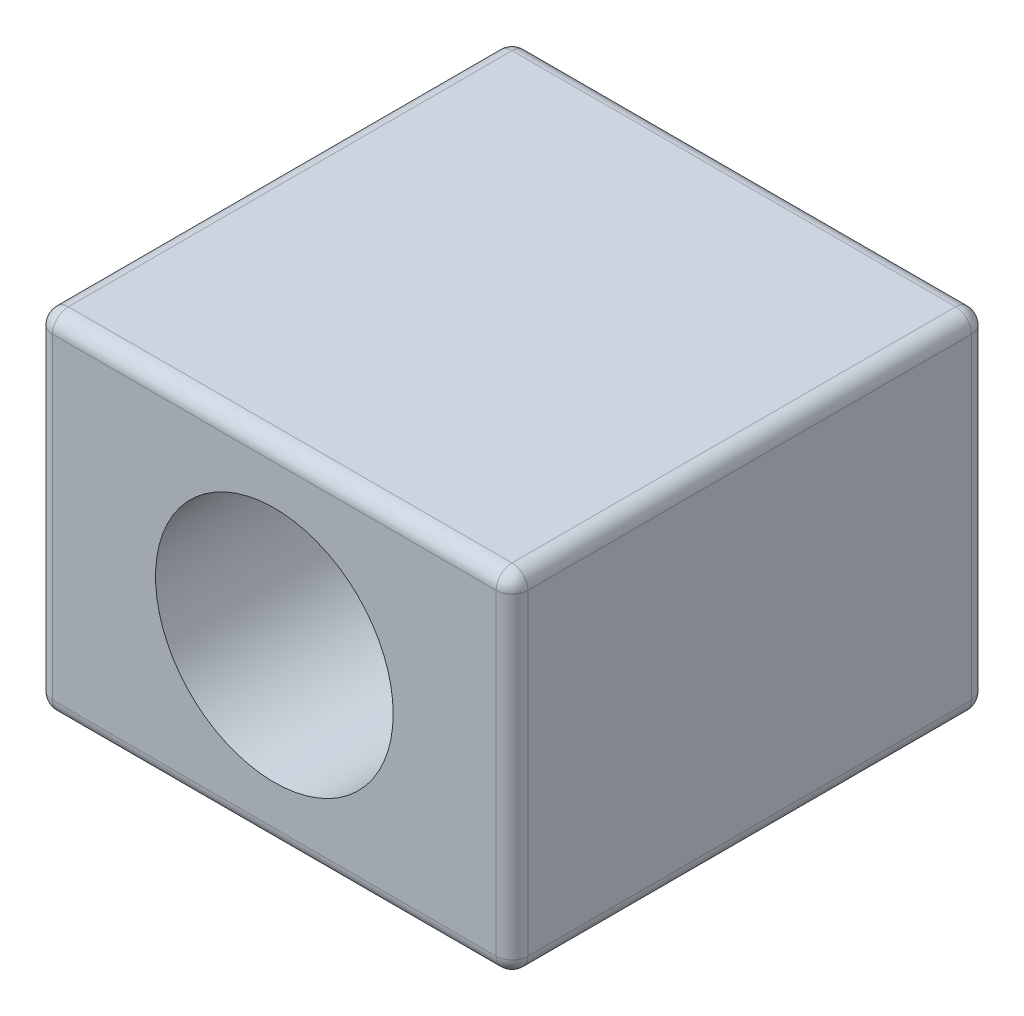
SolidWorks part; units mm, degrees
ref_plane "Front Plane" through (0, 0, 0) normal (0, 0, 1) x (1, 0, 0)
ref_plane "Top Plane" through (0, 0, 0) normal (0, 1, 0) x (1, 0, 0)
ref_plane "Right Plane" through (0, 0, 0) normal (1, 0, 0) x (0, 0, -1)
sketch "Sketch1" plane through (0, 0, 0) normal (0, 0, 1) x (1, 0, 0)
  line L0 (0, -1000) -> (0, 49000) construction
  line L1 (-7.5, 5.5) -> (7.5, 5.5)
  line L2 (-7.5, 5.5) -> (-7.5, -5.5)
  line L3 (-7.5, -5.5) -> (7.5, -5.5)
  line L4 (7.5, 5.5) -> (7.5, -5.5)
  line L5 (-1000, 0) -> (49000, 0) construction
  circle A0 centre (0, 0) radius 3.75
  dimension "D2" = 7.5
  dimension "D1" = 15
extrude "Boss-Extrude1" add sketch "Sketch1" along normal mid plane 15
fillet "Fillet1" radius 0.5 12 edges at (0, -5.5, 7.5) (0, -5.5, -7.5) (7.5, -5.5, 0) (7.5, 0, 7.5) (7.5, 0, -7.5) (7.5, 5.5, 0) (0, 5.5, 7.5) (0, 5.5, -7.5) (-7.5, 5.5, 0) (-7.5, 0, 7.5) (-7.5, -5.5, 0) (-7.5, 0, -7.5)
